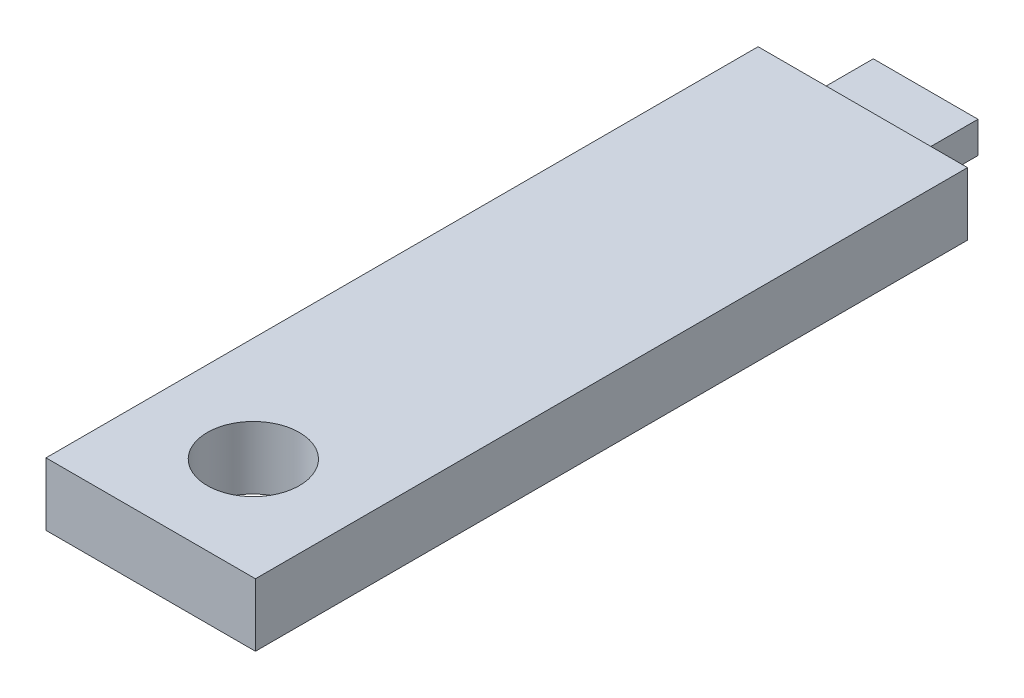
SolidWorks part; units mm, degrees
ref_plane "Front Plane" through (0, 0, 0) normal (0, 0, 1) x (1, 0, 0)
ref_plane "Top Plane" through (0, 0, 0) normal (0, 1, 0) x (1, 0, 0)
ref_plane "Right Plane" through (0, 0, 0) normal (1, 0, 0) x (0, 0, -1)
sketch "Sketch1" plane through (0, 0, 0) normal (0, 0, 1) x (1, 0, 0)
  line L1 (0, 0) -> (5, 0)
  line L2 (0, 0) -> (0, 1.5)
  line L3 (0, 1.5) -> (5, 1.5)
  line L4 (5, 0) -> (5, 1.5)
  dimension "D1" = 5
  dimension "D2" = 1.5
extrude "Boss-Extrude1" add sketch "Sketch1" along normal blind 3
sketch "Sketch2" plane through (0, 0, 3) normal (0, 0, 1) x (1, 0, 0)
  line L0 (0, 0) -> (5, 0) construction
  line L1 (-2.5, -0.75) -> (7.5, -0.75)
  line L2 (-2.5, -0.75) -> (-2.5, 2.25)
  line L3 (-2.5, 2.25) -> (7.5, 2.25)
  line L4 (7.5, -0.75) -> (7.5, 2.25)
  line L5 (0, 1.5) -> (0, 0) construction
  dimension "D1" = 10
  dimension "D2" = 3
  dimension "D3" = 0.75
  dimension "D4" = 2.5
extrude "Boss-Extrude2" add sketch "Sketch2" along normal blind 34
sketch "Sketch3" plane through (0, -0.75, 0) normal (0, -1, 0) x (1, 0, 0)
  circle A0 centre (2.5, 32.1) radius 2.2
  dimension "D1" = 4.4
extrude "Cut-Extrude1" cut sketch "Sketch3" against normal through all
